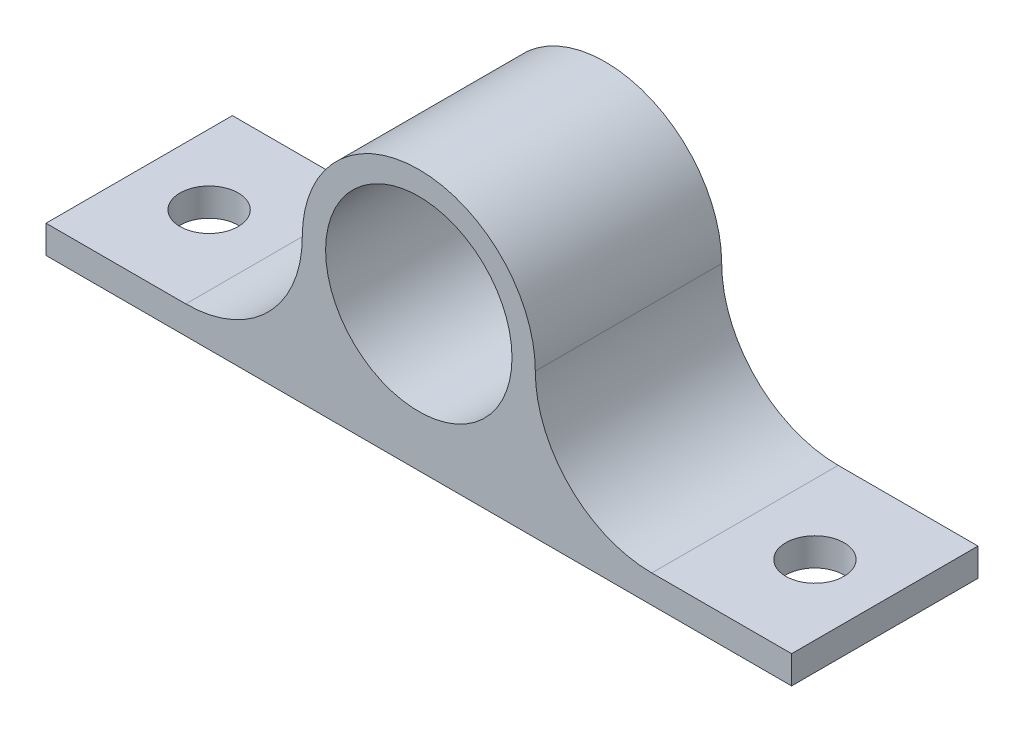
SolidWorks part; units mm, degrees
ref_plane "Front Plane" through (0, 0, 0) normal (0, 0, 1) x (1, 0, 0)
ref_plane "Top Plane" through (0, 0, 0) normal (0, 1, 0) x (1, 0, 0)
ref_plane "Right Plane" through (0, 0, 0) normal (1, 0, 0) x (0, 0, -1)
sketch "Sketch1" plane through (0, 0, 0) normal (0, 0, 1) x (1, 0, 0)
  line L0 (-50.8, -19.685) -> (-50.8, -15.875)
  line L1 (-50.8, -19.685) -> (50.8, -19.685)
  line L2 (-50.8, -15.875) -> (50.8, -15.875)
  line L3 (50.8, -19.685) -> (50.8, -15.875)
  line L4 (-50.8, -19.685) -> (50.8, -15.875) construction
  line L5 (-50.8, -15.875) -> (50.8, -19.685) construction
  line L6 (0, 0) -> (0, -15.875) construction
  line L7 (0, 0) -> (-15.875, 0) construction
  circle A0 centre (0, 0) radius 12.7
  circle A1 centre (0, 0) radius 15.875
  arc A2 (-15.875, 0) -> (-31.75, -15.875) centre (-31.75, 0) cw
  arc A3 (15.875, 0) -> (31.75, -15.875) centre (31.75, 0) ccw
  point P4 (0, -15.875)
  point P5 (0, -17.78)
  dimension "D1" = 25.4
  dimension "D2" = 31.75
  dimension "D3" = 3.81
  dimension "D4" = 101.6
extrude "Boss-Extrude1" add sketch "Sketch1" along normal blind 25.4 contours A1 A0 | A1 A2 L2 | A3 A1 L2 | L1 L3 L2 L0
sketch "Sketch3" plane through (0, -15.875, 0) normal (0, 1, 0) x (1, 0, 0)
  line L0 (-50.8, -12.7) -> (-31.75, -12.7)
  line L1 (-50.8, -25.4) -> (-50.8, 0) construction
  line L2 (-31.75, -25.4) -> (-31.75, 0) construction
  line L3 (-41.275, 0) -> (-41.275, -12.7)
  line L6 (-50.8, 0) -> (-31.75, 0) construction
hole_wizard "5/16 (0.3125) Diameter Hole1" positions "3DSketch3" profile "Sketch5" hole size "5/16" standard "ANSI Inch" end condition through all
sketch3d "3DSketch3"
  point P0 (-41.275, -15.875, 12.7)
sketch "Sketch5" plane through (-41.275, -15.875, 12.7) normal (1, 0, 0) x (0, 0, 1)
  line L0 (0, 0) -> (0, 3.81)
  line L1 (0, 3.81) -> (3.9687, 3.81)
  line L2 (3.9687, 3.81) -> (3.9687, 0)
  line L5 (3.9687, 0) -> (0, 0)
  line L11 (0, -6.35) -> (0, 107.95) construction
  dimension "Thru Hole Dia." = 7.9375
  dimension "Thru Hole Depth" = 3.81
mirror "Mirror1" about plane through (0, 0, 0) normal (1, 0, 0) of "5/16 (0.3125) Diameter Hole1"
